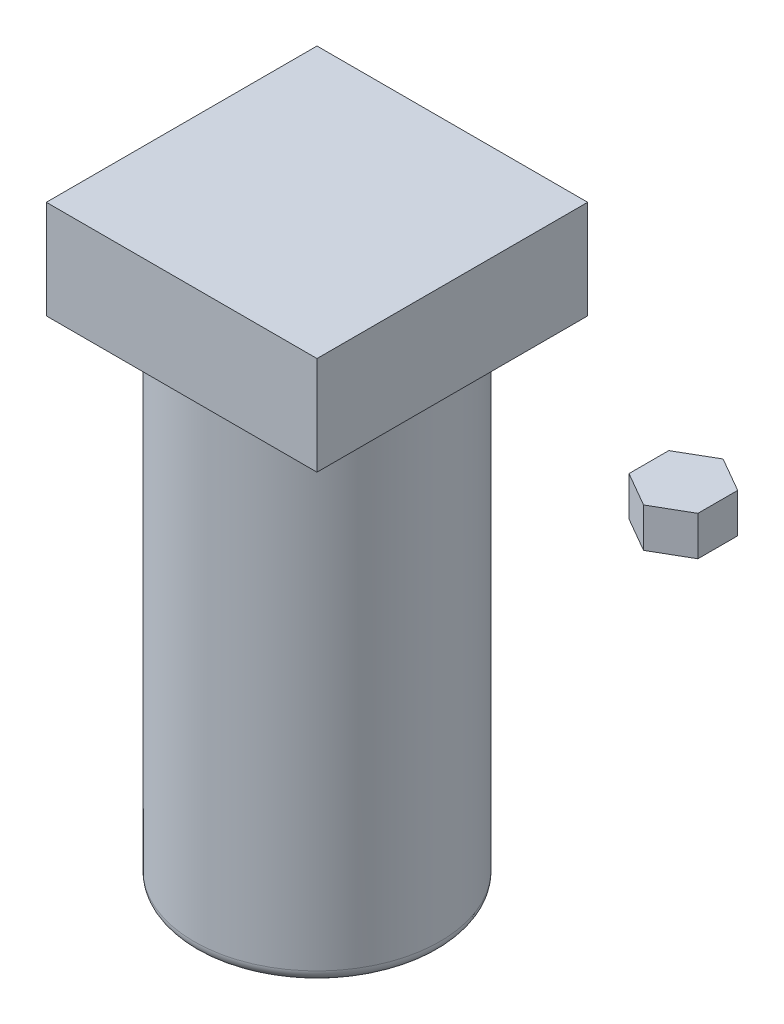
SolidWorks part; units mm, degrees
ref_plane "Front Plane" through (0, 0, 0) normal (0, 0, 1) x (1, 0, 0)
ref_plane "Top Plane" through (0, 0, 0) normal (0, 1, 0) x (1, 0, 0)
ref_plane "Right Plane" through (0, 0, 0) normal (1, 0, 0) x (0, 0, -1)
sketch "Sketch1" plane through (0, 0, 0) normal (0, 1, 0) x (1, 0, 0)
  line L1 (-17.4625, 17.4625) -> (17.4625, 17.4625)
  line L2 (-17.4625, 17.4625) -> (-17.4625, -17.4625)
  line L3 (-17.4625, -17.4625) -> (17.4625, -17.4625)
  line L4 (17.4625, 17.4625) -> (17.4625, -17.4625)
  line L5 (-17.4625, 17.4625) -> (17.4625, -17.4625) construction
  line L6 (-17.4625, -17.4625) -> (17.4625, 17.4625) construction
  point P0 (0, 0)
  dimension "D1" = 34.925
  dimension "D2" = 34.925
extrude "Boss-Extrude1" add sketch "Sketch1" along normal blind 12.7
sketch "Sketch3" plane through (0, 0, 0) normal (0, -1, 0) x (1, 0, 0)
  circle A0 centre (0, 0) radius 15.875
  circle A1 centre (0, 0) radius 12.7
  dimension "D1" = 31.75
  dimension "D2" = 25.4
extrude "Boss-Extrude2" add sketch "Sketch3" along normal blind 63.5
fillet "Fillet1" radius 1.524 1 edges at (0, -63.5, -15.875)
sketch "Sketch5" plane through (0, 0, 0) normal (0, 1, 0) x (1, 0, 0)
  line L1 (47.2711, -5.1326) -> (51.7161, -2.5663)
  line L2 (51.7161, -2.5663) -> (51.7161, 2.5663)
  line L3 (51.7161, 2.5663) -> (47.2711, 5.1326)
  line L4 (47.2711, 5.1326) -> (42.8261, 2.5663)
  line L5 (42.8261, 2.5663) -> (42.8261, -2.5663)
  line L6 (42.8261, -2.5663) -> (47.2711, -5.1326)
  circle A0 centre (47.2711, 0) radius 4.445 construction
  dimension "D1" = 8.89
extrude "Boss-Extrude3" add sketch "Sketch5" along normal blind 5.08 separate body
sketch "Sketch6" plane through (0, 5.08, 0) normal (0, 1, 0) x (1, 0, 0)
  line L0 (47.2711, 5.1326) -> (47.2711, -5.1326) construction
  line L1 (42.8261, 2.5663) -> (51.7161, -2.5663) construction
  line L2 (51.7161, 2.5663) -> (42.8261, -2.5663) construction
  line L3 (42.8261, -2.5663) -> (47.2711, -5.1326) construction
  line L5 (51.7161, 2.5663) -> (47.2711, 5.1326)
  line L6 (47.2711, 5.1326) -> (42.8261, 2.5663)
  line L7 (42.8261, 2.5663) -> (42.8261, -2.5663)
  line L8 (42.8261, -2.5663) -> (47.2711, -5.1326)
  line L9 (47.2711, -5.1326) -> (51.7161, -2.5663)
  line L10 (51.7161, -2.5663) -> (51.7161, 2.5663)
  circle A0 centre (47.2711, 0) radius 4.445
  circle A1 centre (47.2711, 0) radius 4.445 construction
